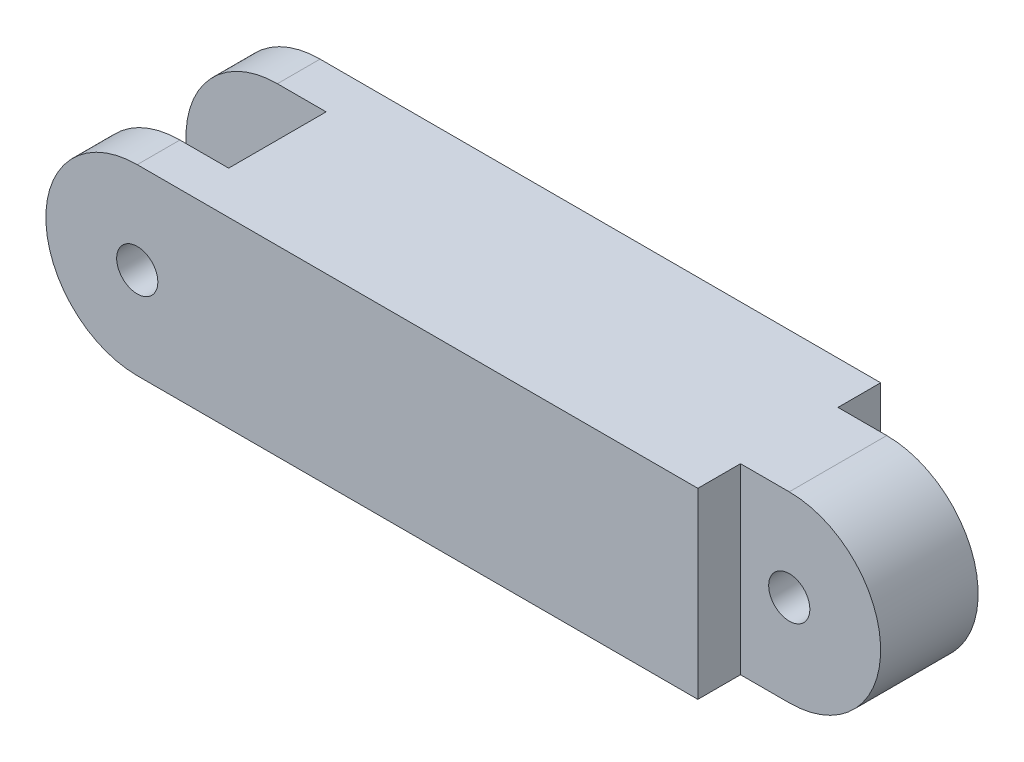
SolidWorks part; units mm, degrees
ref_plane "Front Plane" through (0, 0, 0) normal (0, 0, 1) x (1, 0, 0)
ref_plane "Top Plane" through (0, 0, 0) normal (0, 1, 0) x (1, 0, 0)
ref_plane "Right Plane" through (0, 0, 0) normal (1, 0, 0) x (0, 0, -1)
sketch "Sketch1" plane through (0, 0, 0) normal (0, 0, 1) x (1, 0, 0)
  line L0 (-50, 0) -> (50, 0) construction
  line L1 (-50, 15) -> (50, 15)
  line L2 (-50, -15) -> (50, -15)
  arc A0 (-50, 15) -> (-50, -15) centre (-50, 0) ccw
  arc A1 (50, -15) -> (50, 15) centre (50, 0) ccw
  point P2 (0, 0)
  dimension "D1" = 100
  dimension "D2" = 30
extrude "Boss-Extrude1" add sketch "Sketch1" along normal mid plane 30
hole_wizard "H (0.266) Diameter Hole1" positions "Sketch2" profile "Sketch4" hole size "H" standard "ANSI Inch" end condition through all
sketch "Sketch2" plane through (0, 0, 15) normal (0, 0, 1) x (1, 0, 0)
  point P0 (-50, 0)
  point P3 (50, 0)
sketch "Sketch4" plane through (-50, 0, 15) normal (1, 0, 0) x (0, -1, 0)
  line L0 (0, 0) -> (0, 30)
  line L1 (0, 30) -> (3.3782, 30)
  line L2 (3.3782, 30) -> (3.3782, 0)
  line L5 (3.3782, 0) -> (0, 0)
  line L11 (0, -6.35) -> (0, 107.95) construction
  dimension "Thru Hole Dia." = 6.7564
  dimension "Thru Hole Depth" = 30
sketch "Sketch5" plane through (0, 15, 0) normal (0, 1, 0) x (1, 0, 0)
  line L1 (-82, 8) -> (-42, 8)
  line L2 (-82, 8) -> (-82, -8)
  line L3 (-82, -8) -> (-42, -8)
  line L4 (-42, 8) -> (-42, -8)
  line L5 (-42, 0) -> (0, 0) construction
  line L6 (-50, -15) -> (-50, 15) construction
  line L7 (50, -15) -> (50, 15) construction
  line L8 (42, 28.9161) -> (82, 28.9161)
  line L9 (42, 28.9161) -> (42, 8)
  line L10 (42, 8) -> (82, 8)
  line L11 (82, 28.9161) -> (82, 8)
  line L12 (42, -28.9161) -> (82, -28.9161)
  line L13 (42, -28.9161) -> (42, -8)
  line L14 (42, -8) -> (82, -8)
  line L15 (82, -28.9161) -> (82, -8)
  dimension "D1" = 16
  dimension "D2" = 8
  dimension "D3" = 40
  dimension "D4" = 8
extrude "Cut-Extrude1" cut sketch "Sketch5" against normal through all
